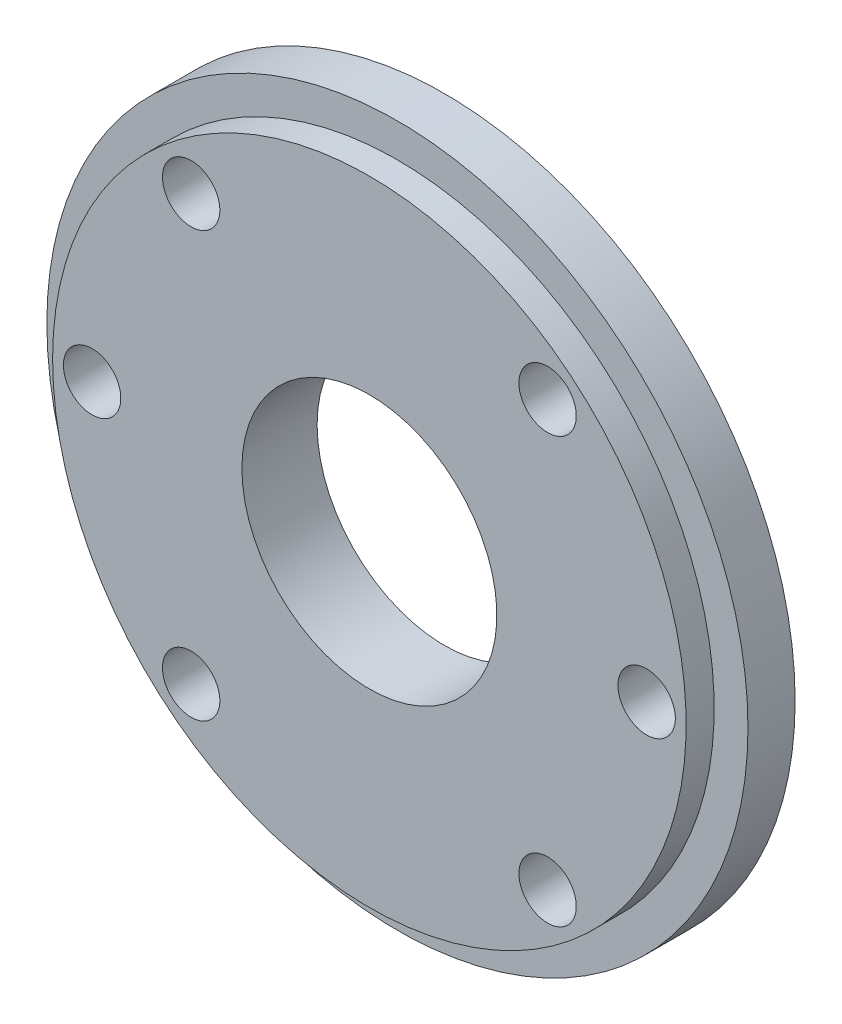
SolidWorks part; units mm, degrees
material "ABS"
ref_plane "前视基准面" through (0, 0, 0) normal (0, 0, 1) x (1, 0, 0)
ref_plane "上视基准面" through (0, 0, 0) normal (0, 1, 0) x (1, 0, 0)
ref_plane "右视基准面" through (0, 0, 0) normal (1, 0, 0) x (0, 0, -1)
sketch "草图1" plane through (0, 0, 0) normal (0, 0, 1) x (1, 0, 0)
  line L0 (-21.75, 0) -> (21.75, 0) construction
  line L1 (0, 0) -> (-13.9806, -16.6615) construction
  line L2 (0, 0) -> (13.9806, 16.6615) construction
  line L3 (-13.9806, 16.6615) -> (0, 0) construction
  line L4 (0, 0) -> (13.9806, -16.6615) construction
  circle A0 centre (0, 0) radius 21.75 construction
  circle A1 centre (0, 0) radius 24.85
  circle A2 centre (-21.75, 0) radius 2.25
  circle A3 centre (-13.9806, 16.6615) radius 2.25
  circle A4 centre (-13.9806, -16.6615) radius 2.25
  circle A5 centre (13.9806, -16.6615) radius 2.25
  circle A6 centre (21.75, 0) radius 2.25
  circle A7 centre (13.9806, 16.6615) radius 2.25
  dimension "D1" = 49.7
  dimension "D2" = 43.5
  dimension "D7" = 4.5
  dimension "D3" = 50
extrude "凸台-拉伸1" add sketch "草图1" along normal blind 6.5
sketch "草图3" plane through (0, 0, 0) normal (0, 0, 1) x (1, 0, 0)
  circle A0 centre (0, 0) radius 24.85 construction
  circle A1 centre (0, 0) radius 24.85
  circle A2 centre (0, 0) radius 27.5
  dimension "D1" = 55
extrude "凸台-拉伸2" add sketch "草图3" along normal blind 4.3
sketch "草图4" plane through (0, 0, 0) normal (0, 0, -1) x (-1, 0, 0)
  circle A0 centre (0, 0) radius 27.5 construction
  circle A1 centre (0, 0) radius 27.5
extrude "切除-拉伸1" cut sketch "草图4" against normal blind 0.6
sketch "草图5" plane through (0, 0, 0.6) normal (0, 0, -1) x (-1, 0, 0)
  circle A0 centre (0, 0) radius 10
  dimension "D1" = 20
extrude "切除-拉伸2" cut sketch "草图5" against normal through all
